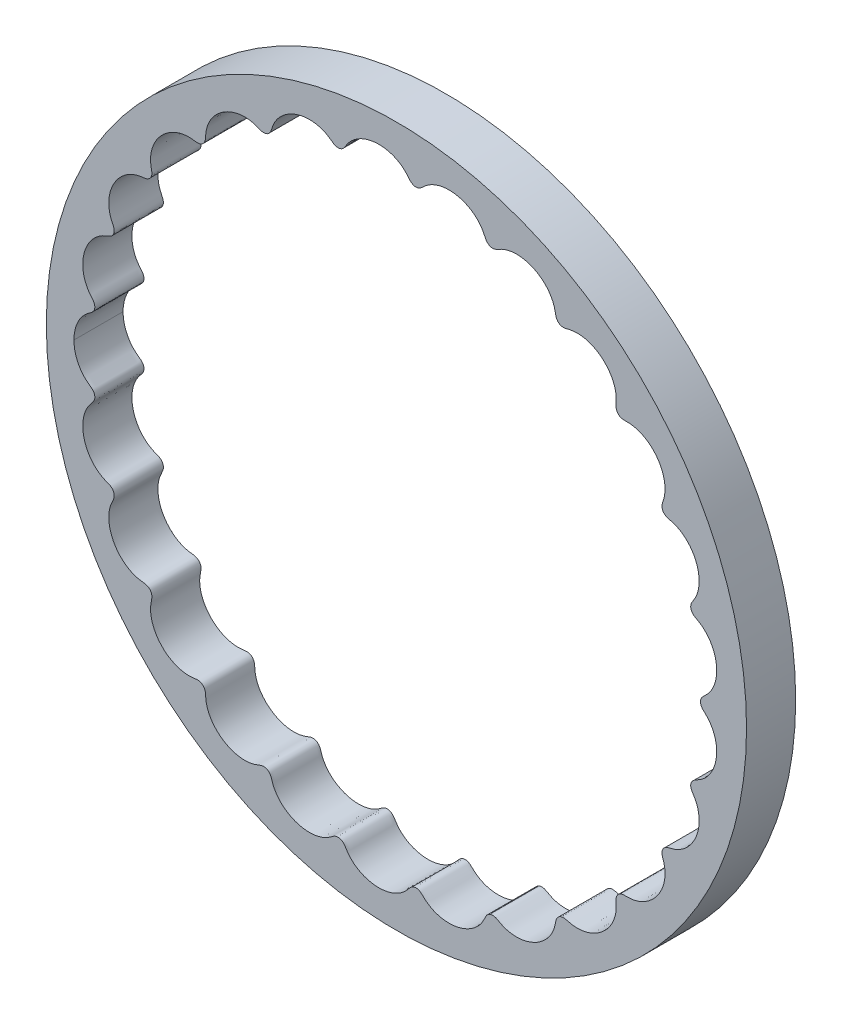
SolidWorks part; units mm, degrees
ref_plane "Plan de face" through (0, 0, 0) normal (0, 0, 1) x (1, 0, 0)
ref_plane "Plan de dessus" through (0, 0, 0) normal (0, 1, 0) x (1, 0, 0)
ref_plane "Plan de droite" through (0, 0, 0) normal (1, 0, 0) x (0, 0, -1)
sketch "Esquisse1" plane through (0, 0, 0) normal (0, 0, 1) x (1, 0, 0)
  line L0 (-1000, 0) -> (49000, 0) construction
  circle A1 centre (0, 0) radius 28.5
  spline S0 degree 4 poles (24.1426, 6.7991) (24.1177, 6.7609) (24.0692, 6.6836) (24.0004, 6.5645) (23.9483, 6.387) (23.9505, 6.1855) (24.0272, 5.9803) (24.1778, 5.8151) (24.3705, 5.7045) (24.5983, 5.5844) (24.8479, 5.4264) (25.1139, 5.2067) (25.3819, 4.9129) (25.6102, 4.583) (25.7961, 4.2235) (25.9371, 3.8403) (26.0305, 3.4429) (26.0756, 3.0373) (26.0716, 2.6291) (26.0179, 2.2244) (25.9151, 1.834) (25.7643, 1.4641) (25.5917, 1.1641) (25.4167, 0.9296) (25.2526, 0.7496) (25.1124, 0.6144) (24.9828, 0.4987) (24.8797, 0.3844) (24.8179, 0.2829) (24.7848, 0.2051) (24.7673, 0.1461) (24.7588, 0.1043) (24.7529, 0.0597) (24.7496, 0.0145) (24.7496, -0.0147) (24.7529, -0.06) (24.7589, -0.1048) (24.7675, -0.1468) (24.7852, -0.2061) (24.8185, -0.2842) (24.8808, -0.3859) (24.9847, -0.5005) (25.1148, -0.6166) (25.2554, -0.7525) (25.4198, -0.9333) (25.595, -1.1691) (25.7689, -1.4729) (25.9207, -1.8497) (26.0235, -2.2499) (26.0747, -2.6669) (26.0733, -3.0863) (26.0204, -3.5015) (25.917, -3.9063) (25.7644, -4.2943) (25.5662, -4.6548) (25.3259, -4.9815) (25.0816, -5.2331) (24.8519, -5.4186) (24.6671, -5.5402) (24.5395, -5.6139) (24.4102, -5.6846) (24.274, -5.758) (24.12, -5.8678) (23.9899, -6.0503) (23.9364, -6.2751) (23.9692, -6.4958) (24.0654, -6.6843) (24.1784, -6.8519) (24.2801, -7.019) (24.3936, -7.2353) (24.5034, -7.5077) (24.5951, -7.8454) (24.647, -8.2482) (24.6457, -8.6612) (24.576, -9.1855) (24.4176, -9.6961) (24.1747, -10.1766) (23.852, -10.6101) (23.5588, -10.9098) (23.241, -11.1578) (22.9466, -11.3291) (22.6921, -11.4408) (22.4727, -11.5135) (22.2939, -11.5615) (22.1013, -11.606) (21.9021, -11.6816) (21.7285, -11.8281) (21.6209, -12.0388) (21.6016, -12.2637) (21.6505, -12.4693) (21.7183, -12.6598) (21.7746, -12.8471) (21.8297, -13.085) (21.8672, -13.3762) (21.8707, -13.726) (21.8195, -14.1287) (21.7142, -14.528) (21.5148, -15.0178) (21.2331, -15.4721) (20.8771, -15.876) (20.4557, -16.2144) (20.0964, -16.4307) (19.7262, -16.5906) (19.3981, -16.6821) (19.1236, -16.7259) (18.8929, -16.7409) (18.7078, -16.7424) (18.5101, -16.7378) (18.2984, -16.7644) (18.0955, -16.8669) (17.9421, -17.0472) (17.8714, -17.2614) (17.8702, -17.4725) (17.8883, -17.6738) (17.8957, -17.8692) (17.8889, -18.1133) (17.8517, -18.4044) (17.7668, -18.7438) (17.6158, -19.1205) (17.4134, -19.4803) (17.1623, -19.8168) (16.8685, -20.1221) (16.5358, -20.3908) (16.1684, -20.6173) (15.771, -20.7957) (15.3688, -20.9145) (14.9702, -20.976) (14.6296, -20.9817) (14.3529, -20.9549) (14.1259, -20.9112) (13.9464, -20.866) (13.7558, -20.8128) (13.5435, -20.7889) (13.3222, -20.8417) (13.1314, -20.9817) (13.013, -21.1736) (12.9618, -21.3782) (12.9291, -21.5776) (12.887, -21.7685) (12.8188, -22.0029) (12.7093, -22.2752) (12.5416, -22.5821) (12.3006, -22.9086) (12.0142, -23.2057) (11.6866, -23.4682) (11.3255, -23.6897) (10.9359, -23.8661) (10.5233, -23.9928) (10.0937, -24.0655) (9.6744, -24.0792) (9.2731, -24.0382) (8.942, -23.9578) (8.6811, -23.862) (8.4724, -23.7624) (8.31, -23.6735) (8.1383, -23.575) (7.9372, -23.5018) (7.7049, -23.5021) (7.4781, -23.6007) (7.3169, -23.7729) (7.2208, -23.9706) (7.1156, -24.2034) (6.9743, -24.4604) (6.773, -24.7375) (6.4979, -25.0224) (6.1834, -25.2709) (5.8357, -25.4797) (5.4603, -25.6452) (5.0615, -25.7656) (4.6447, -25.8371) (4.2157, -25.8559) (3.7816, -25.8181) (3.3723, -25.7258) (2.9942, -25.5849) (2.6941, -25.4236) (2.4656, -25.2649) (2.2891, -25.1158) (2.1537, -24.9891) (2.0123, -24.8511) (1.8324, -24.7331) (1.553, -24.6659) (1.2621, -24.7546) (1.0754, -24.9576) (0.8891, -25.1941) (0.6967, -25.4018) (0.4476, -25.6153) (0.1257, -25.8218) (-0.2246, -25.9871) (-0.599, -26.1091) (-0.9909, -26.1853) (-1.3919, -26.2146) (-1.7962, -26.1958) (-2.1981, -26.1285) (-2.5915, -26.0119) (-2.9628, -25.849) (-3.3062, -25.6424) (-3.6154, -25.3948) (-3.8503, -25.1456) (-4.0231, -24.9087) (-4.157, -24.6911) (-4.2763, -24.5066) (-4.4563, -24.3545) (-4.6931, -24.2829) (-4.9238, -24.3097) (-5.115, -24.4061) (-5.2732, -24.5252) (-5.423, -24.6339) (-5.6174, -24.7592) (-5.864, -24.8876) (-6.1822, -25.0094) (-6.5751, -25.1011) (-6.9928, -25.1407) (-7.4281, -25.1231) (-7.8512, -25.0501) (-8.2556, -24.9263) (-8.636, -24.7563) (-8.9874, -24.5444) (-9.3058, -24.2932) (-9.5861, -24.0067) (-9.8229, -23.6892) (-9.9872, -23.3887) (-10.0948, -23.1158) (-10.1696, -22.8715) (-10.2411, -22.6635) (-10.3812, -22.4737) (-10.595, -22.3493) (-10.8256, -22.322) (-11.0338, -22.3709) (-11.2164, -22.4474) (-11.3887, -22.5149) (-11.6084, -22.5872) (-11.8793, -22.649) (-12.2179, -22.6866) (-12.6212, -22.6763) (-13.0353, -22.6095) (-13.4521, -22.4829) (-13.8453, -22.3049) (-14.2094, -22.0805) (-14.5395, -21.815) (-14.8313, -21.5131) (-15.0777, -21.1819) (-15.2753, -20.8275) (-15.4026, -20.5017) (-15.4765, -20.2177) (-15.5143, -19.9765) (-15.5318, -19.7817) (-15.5392, -19.5798) (-15.5656, -19.3704) (-15.6608, -19.166) (-15.8341, -19.0047) (-16.0476, -18.9266) (-16.2611, -18.9252) (-16.4568, -18.9543) (-16.6405, -18.9763) (-16.8713, -18.9908) (-17.1491, -18.9822) (-17.4862, -18.9332) (-17.8737, -18.8216) (-18.2576, -18.6527) (-18.6291, -18.4253) (-18.9648, -18.1541) (-19.2607, -17.8454) (-19.5135, -17.5053) (-19.7199, -17.1396) (-19.875, -16.7569) (-19.9769, -16.364) (-20.018, -16.0166) (-20.0178, -15.7231) (-19.9934, -15.4801) (-19.9613, -15.2872) (-19.9181, -15.0898) (-19.894, -14.8799) (-19.9394, -14.6589) (-20.0707, -14.462) (-20.2602, -14.3367) (-20.4672, -14.2852) (-20.6639, -14.2651) (-20.8473, -14.2402) (-21.0742, -14.196) (-21.3408, -14.1175) (-21.6546, -13.985) (-22.0015, -13.7794) (-22.3304, -13.5193) (-22.7055, -13.1302) (-23.0074, -12.6844) (-23.2291, -12.1981) (-23.3648, -11.6869) (-23.4186, -11.2774) (-23.4182, -10.8714) (-23.3703, -10.5248) (-23.296, -10.2407) (-23.211, -10.0117) (-23.1314, -9.8331) (-23.0402, -9.6526) (-22.9672, -9.4541) (-22.9601, -9.2287) (-23.0424, -9.0072) (-23.1982, -8.8407) (-23.3889, -8.7414) (-23.5777, -8.6723) (-23.7531, -8.5999) (-23.9662, -8.4963) (-24.2093, -8.3477) (-24.4803, -8.1356) (-24.7613, -7.8463) (-25.0085, -7.5133) (-25.2666, -7.049) (-25.4429, -6.5476) (-25.5339, -6.0256) (-25.5366, -5.4989) (-25.4855, -5.0889) (-25.3828, -4.696) (-25.2489, -4.3726) (-25.1052, -4.1164) (-24.9652, -3.9162) (-24.8431, -3.7634) (-24.7098, -3.6112) (-24.5919, -3.4354) (-24.5338, -3.2206) (-24.5604, -2.9926) (-24.6667, -2.797) (-24.8227, -2.6537) (-24.9897, -2.5393) (-25.1463, -2.4221) (-25.3325, -2.2638) (-25.5023, -2.0873) (-25.6545, -1.8958) (-25.7905, -1.6883) (-25.89, -1.512) (-25.979, -1.3255) (-26.0566, -1.1315) (-26.1214, -0.9307) (-26.1732, -0.7298) (-26.2073, -0.5457) (-26.2284, -0.3959) (-26.2405, -0.2557) (-26.247, -0.1691) (-26.2503, -0.0328) (-26.2503, 0.0323) (-26.2471, 0.1679) (-26.2407, 0.2542) (-26.2286, 0.3933) (-26.2078, 0.5423) (-26.1742, 0.7251) (-26.123, 0.925) (-26.0591, 1.1245) (-25.9824, 1.3176) (-25.8737, 1.547) (-25.7224, 1.8046) (-25.5451, 2.0414) (-25.3437, 2.2529) (-25.1596, 2.4115) (-25.0044, 2.5289) (-24.8386, 2.6423) (-24.6804, 2.7808) (-24.5546, 2.9935) (-24.5303, 3.2355) (-24.6, 3.4498) (-24.7118, 3.6094) (-24.804, 3.7191) (-24.9086, 3.8447) (-25.0204, 3.9911) (-25.1376, 4.1713) (-25.2521, 4.3886) (-25.3469, 4.6153) (-25.4409, 4.9075) (-25.515, 5.269) (-25.5464, 5.6988) (-25.509, 6.1899) (-25.401, 6.6704) (-25.2688, 7.0153) (-25.1588, 7.235) (-25.0985, 7.3418) knots 0 0 0 0 0 0.001685 0.003369 0.005054 0.006738 0.009006 0.011274 0.013086 0.014899 0.018524 0.022149 0.025774 0.029532 0.03329 0.037047 0.040805 0.044562 0.048319 0.052076 0.055834 0.059425 0.063017 0.064813 0.066609 0.068405 0.070201 0.071231 0.072261 0.072776 0.073291 0.073548 0.073806 0.074321 0.074838 0.075097 0.075356 0.075873 0.07639 0.077425 0.07846 0.080263 0.082066 0.083868 0.085671 0.089277 0.092883 0.09675 0.100617 0.104484 0.108351 0.112188 0.116026 0.119864 0.123701 0.127327 0.130952 0.132764 0.134577 0.135483 0.13639 0.138202 0.140296 0.142389 0.144459 0.146528 0.148331 0.150133 0.151935 0.153737 0.157342 0.160946 0.164812 0.168678 0.172544 0.180416 0.184421 0.188427 0.192432 0.195844 0.199256 0.200962 0.202668 0.204374 0.20608 0.208269 0.210458 0.212527 0.214596 0.216398 0.2182 0.220001 0.221803 0.225407 0.22901 0.232875 0.23674 0.240605 0.248477 0.252483 0.256489 0.260496 0.263908 0.26732 0.269026 0.270732 0.272438 0.274144 0.276335 0.278527 0.280595 0.282663 0.284464 0.286266 0.288067 0.289868 0.293471 0.297074 0.300938 0.304802 0.308666 0.31253 0.316537 0.320545 0.324552 0.328559 0.331971 0.335384 0.33709 0.338796 0.340502 0.342208 0.344401 0.346595 0.348662 0.350729 0.35253 0.354331 0.356132 0.357933 0.361536 0.365138 0.369001 0.372864 0.376727 0.38059 0.384598 0.388606 0.392614 0.396623 0.400035 0.403448 0.405154 0.40686 0.408567 0.410273 0.412468 0.414663 0.416905 0.419148 0.420948 0.422747 0.426346 0.429946 0.433545 0.437321 0.441097 0.444873 0.44865 0.452659 0.456668 0.460677 0.464686 0.468099 0.471512 0.473218 0.474925 0.476631 0.478338 0.480534 0.48273 0.48702 0.488749 0.490478 0.493937 0.497395 0.500854 0.50453 0.508207 0.511883 0.515559 0.519335 0.523111 0.526887 0.530662 0.534262 0.537861 0.54146 0.543259 0.545059 0.547301 0.549542 0.551738 0.553933 0.55564 0.557346 0.559053 0.560759 0.564172 0.567585 0.571593 0.575602 0.57961 0.583619 0.587396 0.591172 0.594949 0.598726 0.602325 0.605924 0.609523 0.611323 0.613123 0.615366 0.61761 0.619804 0.621998 0.623704 0.625411 0.627117 0.628823 0.632235 0.635648 0.639656 0.643663 0.647671 0.651679 0.655542 0.659406 0.663269 0.667133 0.670735 0.674338 0.676139 0.67794 0.679742 0.681543 0.68361 0.685678 0.68787 0.690063 0.691769 0.693475 0.695181 0.696887 0.700299 0.703711 0.707718 0.711725 0.715732 0.719739 0.723603 0.727468 0.731332 0.735197 0.7388 0.742403 0.744204 0.746006 0.747808 0.749609 0.751678 0.753746 0.755937 0.758127 0.759833 0.761539 0.763245 0.764951 0.768363 0.771775 0.775781 0.779787 0.783793 0.791664 0.795529 0.799395 0.80326 0.806864 0.810468 0.81227 0.814073 0.815875 0.817677 0.819746 0.821815 0.823999 0.826183 0.827931 0.82968 0.831429 0.833177 0.836675 0.840172 0.844094 0.848015 0.851937 0.859725 0.863591 0.867458 0.871324 0.874929 0.878534 0.880337 0.882139 0.883942 0.885745 0.887814 0.889884 0.891953 0.894023 0.895826 0.897629 0.899432 0.901235 0.904841 0.906644 0.908448 0.910381 0.912315 0.914249 0.916183 0.918117 0.92005 0.921017 0.921984 0.922951 0.923918 0.924879 0.925839 0.9268 0.927761 0.929682 0.931604 0.933525 0.935447 0.937368 0.93929 0.942875 0.94646 0.948253 0.950045 0.951838 0.95363 0.955683 0.957735 0.960756 0.962266 0.963777 0.964909 0.96604 0.968304 0.970568 0.972832 0.975095 0.977359 0.981887 0.986415 0.990943 0.995472 1 1 1 1 1 construction
  spline S1 degree 4 poles (24.75, 0) (24.75, -0.0119) (24.7507, -0.0298) (24.7529, -0.06) (24.7589, -0.1048) (24.7675, -0.1468) (24.7852, -0.2061) (24.8185, -0.2842) (24.8808, -0.3859) (24.9847, -0.5005) (25.1148, -0.6166) (25.2554, -0.7525) (25.4198, -0.9333) (25.595, -1.1691) (25.7689, -1.4729) (25.9207, -1.8497) (26.0235, -2.2499) (26.0747, -2.6669) (26.0733, -3.0863) (26.0204, -3.5015) (25.917, -3.9063) (25.7644, -4.2943) (25.5662, -4.6548) (25.3259, -4.9815) (25.0816, -5.2331) (24.8519, -5.4186) (24.6671, -5.5402) (24.5395, -5.6139) (24.4102, -5.6846) (24.274, -5.758) (24.12, -5.8678) (23.9899, -6.0503) (23.9364, -6.2751) (23.9692, -6.4958) (24.0654, -6.6843) (24.1784, -6.8519) (24.2801, -7.019) (24.3936, -7.2353) (24.5034, -7.5077) (24.5951, -7.8454) (24.647, -8.2482) (24.6457, -8.6612) (24.576, -9.1855) (24.4176, -9.6961) (24.1747, -10.1766) (23.852, -10.6101) (23.5588, -10.9098) (23.241, -11.1578) (22.9466, -11.3291) (22.6921, -11.4408) (22.4727, -11.5135) (22.2939, -11.5615) (22.1013, -11.606) (21.9021, -11.6816) (21.7285, -11.8281) (21.6209, -12.0388) (21.6016, -12.2637) (21.6505, -12.4693) (21.7183, -12.6598) (21.7746, -12.8471) (21.8297, -13.085) (21.8672, -13.3762) (21.8707, -13.726) (21.8195, -14.1287) (21.7142, -14.528) (21.5148, -15.0178) (21.2331, -15.4721) (20.8771, -15.876) (20.4557, -16.2144) (20.0964, -16.4307) (19.7262, -16.5906) (19.3981, -16.6821) (19.1236, -16.7259) (18.8929, -16.7409) (18.7078, -16.7424) (18.5101, -16.7378) (18.2984, -16.7644) (18.0955, -16.8669) (17.9421, -17.0472) (17.8714, -17.2614) (17.8702, -17.4725) (17.8883, -17.6738) (17.8957, -17.8692) (17.8889, -18.1133) (17.8517, -18.4044) (17.7668, -18.7438) (17.6158, -19.1205) (17.4134, -19.4803) (17.1623, -19.8168) (16.8685, -20.1221) (16.5358, -20.3908) (16.1684, -20.6173) (15.771, -20.7957) (15.3688, -20.9145) (14.9702, -20.976) (14.6296, -20.9817) (14.3529, -20.9549) (14.1259, -20.9112) (13.9464, -20.866) (13.7558, -20.8128) (13.5435, -20.7889) (13.3222, -20.8417) (13.1314, -20.9817) (13.013, -21.1736) (12.9618, -21.3782) (12.9291, -21.5776) (12.887, -21.7685) (12.8188, -22.0029) (12.7093, -22.2752) (12.5416, -22.5821) (12.3006, -22.9086) (12.0142, -23.2057) (11.6866, -23.4682) (11.3255, -23.6897) (10.9359, -23.8661) (10.5233, -23.9928) (10.0937, -24.0655) (9.6744, -24.0792) (9.2731, -24.0382) (8.942, -23.9578) (8.6811, -23.862) (8.4724, -23.7624) (8.31, -23.6735) (8.1383, -23.575) (7.9372, -23.5018) (7.7049, -23.5021) (7.4781, -23.6007) (7.3169, -23.7729) (7.2208, -23.9706) (7.1156, -24.2034) (6.9743, -24.4604) (6.773, -24.7375) (6.4979, -25.0224) (6.1834, -25.2709) (5.8357, -25.4797) (5.4603, -25.6452) (5.0615, -25.7656) (4.6447, -25.8371) (4.2157, -25.8559) (3.7816, -25.8181) (3.3723, -25.7258) (2.9942, -25.5849) (2.6941, -25.4236) (2.4656, -25.2649) (2.2891, -25.1158) (2.1537, -24.9891) (2.0123, -24.8511) (1.8324, -24.7331) (1.553, -24.6659) (1.2621, -24.7546) (1.0754, -24.9576) (0.8891, -25.1941) (0.6967, -25.4018) (0.4476, -25.6153) (0.1257, -25.8218) (-0.2246, -25.9871) (-0.599, -26.1091) (-0.9909, -26.1853) (-1.3919, -26.2146) (-1.7962, -26.1958) (-2.1981, -26.1285) (-2.5915, -26.0119) (-2.9628, -25.849) (-3.3062, -25.6424) (-3.6154, -25.3948) (-3.8503, -25.1456) (-4.0231, -24.9087) (-4.157, -24.6911) (-4.2763, -24.5066) (-4.4563, -24.3545) (-4.6931, -24.2829) (-4.9238, -24.3097) (-5.115, -24.4061) (-5.2732, -24.5252) (-5.423, -24.6339) (-5.6174, -24.7592) (-5.864, -24.8876) (-6.1822, -25.0094) (-6.5751, -25.1011) (-6.9928, -25.1407) (-7.4281, -25.1231) (-7.8512, -25.0501) (-8.2556, -24.9263) (-8.636, -24.7563) (-8.9874, -24.5444) (-9.3058, -24.2932) (-9.5861, -24.0067) (-9.8229, -23.6892) (-9.9872, -23.3887) (-10.0948, -23.1158) (-10.1696, -22.8715) (-10.2411, -22.6635) (-10.3812, -22.4737) (-10.595, -22.3493) (-10.8256, -22.322) (-11.0338, -22.3709) (-11.2164, -22.4474) (-11.3887, -22.5149) (-11.6084, -22.5872) (-11.8793, -22.649) (-12.2179, -22.6866) (-12.6212, -22.6763) (-13.0353, -22.6095) (-13.4521, -22.4829) (-13.8453, -22.3049) (-14.2094, -22.0805) (-14.5395, -21.815) (-14.8313, -21.5131) (-15.0777, -21.1819) (-15.2753, -20.8275) (-15.4026, -20.5017) (-15.4765, -20.2177) (-15.5143, -19.9765) (-15.5318, -19.7817) (-15.5392, -19.5798) (-15.5656, -19.3704) (-15.6608, -19.166) (-15.8341, -19.0047) (-16.0476, -18.9266) (-16.2611, -18.9252) (-16.4568, -18.9543) (-16.6405, -18.9763) (-16.8713, -18.9908) (-17.1491, -18.9822) (-17.4862, -18.9332) (-17.8737, -18.8216) (-18.2576, -18.6527) (-18.6291, -18.4253) (-18.9648, -18.1541) (-19.2607, -17.8454) (-19.5135, -17.5053) (-19.7199, -17.1396) (-19.875, -16.7569) (-19.9769, -16.364) (-20.018, -16.0166) (-20.0178, -15.7231) (-19.9934, -15.4801) (-19.9613, -15.2872) (-19.9181, -15.0898) (-19.894, -14.8799) (-19.9394, -14.6589) (-20.0707, -14.462) (-20.2602, -14.3367) (-20.4672, -14.2852) (-20.6639, -14.2651) (-20.8473, -14.2402) (-21.0742, -14.196) (-21.3408, -14.1175) (-21.6546, -13.985) (-22.0015, -13.7794) (-22.3304, -13.5193) (-22.7055, -13.1302) (-23.0074, -12.6844) (-23.2291, -12.1981) (-23.3648, -11.6869) (-23.4186, -11.2774) (-23.4182, -10.8714) (-23.3703, -10.5248) (-23.296, -10.2407) (-23.211, -10.0117) (-23.1314, -9.8331) (-23.0402, -9.6526) (-22.9672, -9.4541) (-22.9601, -9.2287) (-23.0424, -9.0072) (-23.1982, -8.8407) (-23.3889, -8.7414) (-23.5777, -8.6723) (-23.7531, -8.5999) (-23.9662, -8.4963) (-24.2093, -8.3477) (-24.4803, -8.1356) (-24.7613, -7.8463) (-25.0085, -7.5133) (-25.2666, -7.049) (-25.4429, -6.5476) (-25.5339, -6.0256) (-25.5366, -5.4989) (-25.4855, -5.0889) (-25.3828, -4.696) (-25.2489, -4.3726) (-25.1052, -4.1164) (-24.9652, -3.9162) (-24.8431, -3.7634) (-24.7098, -3.6112) (-24.5919, -3.4354) (-24.5338, -3.2206) (-24.5604, -2.9926) (-24.6667, -2.797) (-24.8227, -2.6537) (-24.9897, -2.5393) (-25.1463, -2.4221) (-25.3325, -2.2638) (-25.5023, -2.0873) (-25.6545, -1.8958) (-25.7905, -1.6883) (-25.89, -1.512) (-25.979, -1.3255) (-26.0566, -1.1315) (-26.1214, -0.9307) (-26.1732, -0.7298) (-26.2073, -0.5457) (-26.2284, -0.3959) (-26.2405, -0.2557) (-26.247, -0.1691) (-26.2495, -0.0667) (-26.25, -0.0223) (-26.25, 0) knots 0.074321 0.074321 0.074321 0.074321 0.074321 0.074838 0.075097 0.075356 0.075873 0.07639 0.077425 0.07846 0.080263 0.082066 0.083868 0.085671 0.089277 0.092883 0.09675 0.100617 0.104484 0.108351 0.112188 0.116026 0.119864 0.123701 0.127327 0.130952 0.132764 0.134577 0.135483 0.13639 0.138202 0.140296 0.142389 0.144459 0.146528 0.148331 0.150133 0.151935 0.153737 0.157342 0.160946 0.164812 0.168678 0.172544 0.180416 0.184421 0.188427 0.192432 0.195844 0.199256 0.200962 0.202668 0.204374 0.20608 0.208269 0.210458 0.212527 0.214596 0.216398 0.2182 0.220001 0.221803 0.225407 0.22901 0.232875 0.23674 0.240605 0.248477 0.252483 0.256489 0.260496 0.263908 0.26732 0.269026 0.270732 0.272438 0.274144 0.276335 0.278527 0.280595 0.282663 0.284464 0.286266 0.288067 0.289868 0.293471 0.297074 0.300938 0.304802 0.308666 0.31253 0.316537 0.320545 0.324552 0.328559 0.331971 0.335384 0.33709 0.338796 0.340502 0.342208 0.344401 0.346595 0.348662 0.350729 0.35253 0.354331 0.356132 0.357933 0.361536 0.365138 0.369001 0.372864 0.376727 0.38059 0.384598 0.388606 0.392614 0.396623 0.400035 0.403448 0.405154 0.40686 0.408567 0.410273 0.412468 0.414663 0.416905 0.419148 0.420948 0.422747 0.426346 0.429946 0.433545 0.437321 0.441097 0.444873 0.44865 0.452659 0.456668 0.460677 0.464686 0.468099 0.471512 0.473218 0.474925 0.476631 0.478338 0.480534 0.48273 0.48702 0.488749 0.490478 0.493937 0.497395 0.500854 0.50453 0.508207 0.511883 0.515559 0.519335 0.523111 0.526887 0.530662 0.534262 0.537861 0.54146 0.543259 0.545059 0.547301 0.549542 0.551738 0.553933 0.55564 0.557346 0.559053 0.560759 0.564172 0.567585 0.571593 0.575602 0.57961 0.583619 0.587396 0.591172 0.594949 0.598726 0.602325 0.605924 0.609523 0.611323 0.613123 0.615366 0.61761 0.619804 0.621998 0.623704 0.625411 0.627117 0.628823 0.632235 0.635648 0.639656 0.643663 0.647671 0.651679 0.655542 0.659406 0.663269 0.667133 0.670735 0.674338 0.676139 0.67794 0.679742 0.681543 0.68361 0.685678 0.68787 0.690063 0.691769 0.693475 0.695181 0.696887 0.700299 0.703711 0.707718 0.711725 0.715732 0.719739 0.723603 0.727468 0.731332 0.735197 0.7388 0.742403 0.744204 0.746006 0.747808 0.749609 0.751678 0.753746 0.755937 0.758127 0.759833 0.761539 0.763245 0.764951 0.768363 0.771775 0.775781 0.779787 0.783793 0.791664 0.795529 0.799395 0.80326 0.806864 0.810468 0.81227 0.814073 0.815875 0.817677 0.819746 0.821815 0.823999 0.826183 0.827931 0.82968 0.831429 0.833177 0.836675 0.840172 0.844094 0.848015 0.851937 0.859725 0.863591 0.867458 0.871324 0.874929 0.878534 0.880337 0.882139 0.883942 0.885745 0.887814 0.889884 0.891953 0.894023 0.895826 0.897629 0.899432 0.901235 0.904841 0.906644 0.908448 0.910381 0.912315 0.914249 0.916183 0.918117 0.92005 0.921017 0.921984 0.922951 0.923918 0.923918 0.923918 0.923918 0.923918
  spline S2 degree 4 poles (24.75, 0) (24.75, 0.0119) (24.7507, 0.0298) (24.7529, 0.06) (24.7589, 0.1048) (24.7675, 0.1468) (24.7852, 0.2061) (24.8185, 0.2842) (24.8808, 0.3859) (24.9847, 0.5005) (25.1148, 0.6166) (25.2554, 0.7525) (25.4198, 0.9333) (25.595, 1.1691) (25.7689, 1.4729) (25.9207, 1.8497) (26.0235, 2.2499) (26.0747, 2.6669) (26.0733, 3.0863) (26.0204, 3.5015) (25.917, 3.9063) (25.7644, 4.2943) (25.5662, 4.6548) (25.3259, 4.9815) (25.0816, 5.2331) (24.8519, 5.4186) (24.6671, 5.5402) (24.5395, 5.6139) (24.4102, 5.6846) (24.274, 5.758) (24.12, 5.8678) (23.9899, 6.0503) (23.9364, 6.2751) (23.9692, 6.4958) (24.0654, 6.6843) (24.1784, 6.8519) (24.2801, 7.019) (24.3936, 7.2353) (24.5034, 7.5077) (24.5951, 7.8454) (24.647, 8.2482) (24.6457, 8.6612) (24.576, 9.1855) (24.4176, 9.6961) (24.1747, 10.1766) (23.852, 10.6101) (23.5588, 10.9098) (23.241, 11.1578) (22.9466, 11.3291) (22.6921, 11.4408) (22.4727, 11.5135) (22.2939, 11.5615) (22.1013, 11.606) (21.9021, 11.6816) (21.7285, 11.8281) (21.6209, 12.0388) (21.6016, 12.2637) (21.6505, 12.4693) (21.7183, 12.6598) (21.7746, 12.8471) (21.8297, 13.085) (21.8672, 13.3762) (21.8707, 13.726) (21.8195, 14.1287) (21.7142, 14.528) (21.5148, 15.0178) (21.2331, 15.4721) (20.8771, 15.876) (20.4557, 16.2144) (20.0964, 16.4307) (19.7262, 16.5906) (19.3981, 16.6821) (19.1236, 16.7259) (18.8929, 16.7409) (18.7078, 16.7424) (18.5101, 16.7378) (18.2984, 16.7644) (18.0955, 16.8669) (17.9421, 17.0472) (17.8714, 17.2614) (17.8702, 17.4725) (17.8883, 17.6738) (17.8957, 17.8692) (17.8889, 18.1133) (17.8517, 18.4044) (17.7668, 18.7438) (17.6158, 19.1205) (17.4134, 19.4803) (17.1623, 19.8168) (16.8685, 20.1221) (16.5358, 20.3908) (16.1684, 20.6173) (15.771, 20.7957) (15.3688, 20.9145) (14.9702, 20.976) (14.6296, 20.9817) (14.3529, 20.9549) (14.1259, 20.9112) (13.9464, 20.866) (13.7558, 20.8128) (13.5435, 20.7889) (13.3222, 20.8417) (13.1314, 20.9817) (13.013, 21.1736) (12.9618, 21.3782) (12.9291, 21.5776) (12.887, 21.7685) (12.8188, 22.0029) (12.7093, 22.2752) (12.5416, 22.5821) (12.3006, 22.9086) (12.0142, 23.2057) (11.6866, 23.4682) (11.3255, 23.6897) (10.9359, 23.8661) (10.5233, 23.9928) (10.0937, 24.0655) (9.6744, 24.0792) (9.2731, 24.0382) (8.942, 23.9578) (8.6811, 23.862) (8.4724, 23.7624) (8.31, 23.6735) (8.1383, 23.575) (7.9372, 23.5018) (7.7049, 23.5021) (7.4781, 23.6007) (7.3169, 23.7729) (7.2208, 23.9706) (7.1156, 24.2034) (6.9743, 24.4604) (6.773, 24.7375) (6.4979, 25.0224) (6.1834, 25.2709) (5.8357, 25.4797) (5.4603, 25.6452) (5.0615, 25.7656) (4.6447, 25.8371) (4.2157, 25.8559) (3.7816, 25.8181) (3.3723, 25.7258) (2.9942, 25.5849) (2.6941, 25.4236) (2.4656, 25.2649) (2.2891, 25.1158) (2.1537, 24.9891) (2.0123, 24.8511) (1.8324, 24.7331) (1.553, 24.6659) (1.2621, 24.7546) (1.0754, 24.9576) (0.8891, 25.1941) (0.6967, 25.4018) (0.4476, 25.6153) (0.1257, 25.8218) (-0.2246, 25.9871) (-0.599, 26.1091) (-0.9909, 26.1853) (-1.3919, 26.2146) (-1.7962, 26.1958) (-2.1981, 26.1285) (-2.5915, 26.0119) (-2.9628, 25.849) (-3.3062, 25.6424) (-3.6154, 25.3948) (-3.8503, 25.1456) (-4.0231, 24.9087) (-4.157, 24.6911) (-4.2763, 24.5066) (-4.4563, 24.3545) (-4.6931, 24.2829) (-4.9238, 24.3097) (-5.115, 24.4061) (-5.2732, 24.5252) (-5.423, 24.6339) (-5.6174, 24.7592) (-5.864, 24.8876) (-6.1822, 25.0094) (-6.5751, 25.1011) (-6.9928, 25.1407) (-7.4281, 25.1231) (-7.8512, 25.0501) (-8.2556, 24.9263) (-8.636, 24.7563) (-8.9874, 24.5444) (-9.3058, 24.2932) (-9.5861, 24.0067) (-9.8229, 23.6892) (-9.9872, 23.3887) (-10.0948, 23.1158) (-10.1696, 22.8715) (-10.2411, 22.6635) (-10.3812, 22.4737) (-10.595, 22.3493) (-10.8256, 22.322) (-11.0338, 22.3709) (-11.2164, 22.4474) (-11.3887, 22.5149) (-11.6084, 22.5872) (-11.8793, 22.649) (-12.2179, 22.6866) (-12.6212, 22.6763) (-13.0353, 22.6095) (-13.4521, 22.4829) (-13.8453, 22.3049) (-14.2094, 22.0805) (-14.5395, 21.815) (-14.8313, 21.5131) (-15.0777, 21.1819) (-15.2753, 20.8275) (-15.4026, 20.5017) (-15.4765, 20.2177) (-15.5143, 19.9765) (-15.5318, 19.7817) (-15.5392, 19.5798) (-15.5656, 19.3704) (-15.6608, 19.166) (-15.8341, 19.0047) (-16.0476, 18.9266) (-16.2611, 18.9252) (-16.4568, 18.9543) (-16.6405, 18.9763) (-16.8713, 18.9908) (-17.1491, 18.9822) (-17.4862, 18.9332) (-17.8737, 18.8216) (-18.2576, 18.6527) (-18.6291, 18.4253) (-18.9648, 18.1541) (-19.2607, 17.8454) (-19.5135, 17.5053) (-19.7199, 17.1396) (-19.875, 16.7569) (-19.9769, 16.364) (-20.018, 16.0166) (-20.0178, 15.7231) (-19.9934, 15.4801) (-19.9613, 15.2872) (-19.9181, 15.0898) (-19.894, 14.8799) (-19.9394, 14.6589) (-20.0707, 14.462) (-20.2602, 14.3367) (-20.4672, 14.2852) (-20.6639, 14.2651) (-20.8473, 14.2402) (-21.0742, 14.196) (-21.3408, 14.1175) (-21.6546, 13.985) (-22.0015, 13.7794) (-22.3304, 13.5193) (-22.7055, 13.1302) (-23.0074, 12.6844) (-23.2291, 12.1981) (-23.3648, 11.6869) (-23.4186, 11.2774) (-23.4182, 10.8714) (-23.3703, 10.5248) (-23.296, 10.2407) (-23.211, 10.0117) (-23.1314, 9.8331) (-23.0402, 9.6526) (-22.9672, 9.4541) (-22.9601, 9.2287) (-23.0424, 9.0072) (-23.1982, 8.8407) (-23.3889, 8.7414) (-23.5777, 8.6723) (-23.7531, 8.5999) (-23.9662, 8.4963) (-24.2093, 8.3477) (-24.4803, 8.1356) (-24.7613, 7.8463) (-25.0085, 7.5133) (-25.2666, 7.049) (-25.4429, 6.5476) (-25.5339, 6.0256) (-25.5366, 5.4989) (-25.4855, 5.0889) (-25.3828, 4.696) (-25.2489, 4.3726) (-25.1052, 4.1164) (-24.9652, 3.9162) (-24.8431, 3.7634) (-24.7098, 3.6112) (-24.5919, 3.4354) (-24.5338, 3.2206) (-24.5604, 2.9926) (-24.6667, 2.797) (-24.8227, 2.6537) (-24.9897, 2.5393) (-25.1463, 2.4221) (-25.3325, 2.2638) (-25.5023, 2.0873) (-25.6545, 1.8958) (-25.7905, 1.6883) (-25.89, 1.512) (-25.979, 1.3255) (-26.0566, 1.1315) (-26.1214, 0.9307) (-26.1732, 0.7298) (-26.2073, 0.5457) (-26.2284, 0.3959) (-26.2405, 0.2557) (-26.247, 0.1691) (-26.2495, 0.0667) (-26.25, 0.0223) (-26.25, 0) knots 0.074321 0.074321 0.074321 0.074321 0.074321 0.074838 0.075097 0.075356 0.075873 0.07639 0.077425 0.07846 0.080263 0.082066 0.083868 0.085671 0.089277 0.092883 0.09675 0.100617 0.104484 0.108351 0.112188 0.116026 0.119864 0.123701 0.127327 0.130952 0.132764 0.134577 0.135483 0.13639 0.138202 0.140296 0.142389 0.144459 0.146528 0.148331 0.150133 0.151935 0.153737 0.157342 0.160946 0.164812 0.168678 0.172544 0.180416 0.184421 0.188427 0.192432 0.195844 0.199256 0.200962 0.202668 0.204374 0.20608 0.208269 0.210458 0.212527 0.214596 0.216398 0.2182 0.220001 0.221803 0.225407 0.22901 0.232875 0.23674 0.240605 0.248477 0.252483 0.256489 0.260496 0.263908 0.26732 0.269026 0.270732 0.272438 0.274144 0.276335 0.278527 0.280595 0.282663 0.284464 0.286266 0.288067 0.289868 0.293471 0.297074 0.300938 0.304802 0.308666 0.31253 0.316537 0.320545 0.324552 0.328559 0.331971 0.335384 0.33709 0.338796 0.340502 0.342208 0.344401 0.346595 0.348662 0.350729 0.35253 0.354331 0.356132 0.357933 0.361536 0.365138 0.369001 0.372864 0.376727 0.38059 0.384598 0.388606 0.392614 0.396623 0.400035 0.403448 0.405154 0.40686 0.408567 0.410273 0.412468 0.414663 0.416905 0.419148 0.420948 0.422747 0.426346 0.429946 0.433545 0.437321 0.441097 0.444873 0.44865 0.452659 0.456668 0.460677 0.464686 0.468099 0.471512 0.473218 0.474925 0.476631 0.478338 0.480534 0.48273 0.48702 0.488749 0.490478 0.493937 0.497395 0.500854 0.50453 0.508207 0.511883 0.515559 0.519335 0.523111 0.526887 0.530662 0.534262 0.537861 0.54146 0.543259 0.545059 0.547301 0.549542 0.551738 0.553933 0.55564 0.557346 0.559053 0.560759 0.564172 0.567585 0.571593 0.575602 0.57961 0.583619 0.587396 0.591172 0.594949 0.598726 0.602325 0.605924 0.609523 0.611323 0.613123 0.615366 0.61761 0.619804 0.621998 0.623704 0.625411 0.627117 0.628823 0.632235 0.635648 0.639656 0.643663 0.647671 0.651679 0.655542 0.659406 0.663269 0.667133 0.670735 0.674338 0.676139 0.67794 0.679742 0.681543 0.68361 0.685678 0.68787 0.690063 0.691769 0.693475 0.695181 0.696887 0.700299 0.703711 0.707718 0.711725 0.715732 0.719739 0.723603 0.727468 0.731332 0.735197 0.7388 0.742403 0.744204 0.746006 0.747808 0.749609 0.751678 0.753746 0.755937 0.758127 0.759833 0.761539 0.763245 0.764951 0.768363 0.771775 0.775781 0.779787 0.783793 0.791664 0.795529 0.799395 0.80326 0.806864 0.810468 0.81227 0.814073 0.815875 0.817677 0.819746 0.821815 0.823999 0.826183 0.827931 0.82968 0.831429 0.833177 0.836675 0.840172 0.844094 0.848015 0.851937 0.859725 0.863591 0.867458 0.871324 0.874929 0.878534 0.880337 0.882139 0.883942 0.885745 0.887814 0.889884 0.891953 0.894023 0.895826 0.897629 0.899432 0.901235 0.904841 0.906644 0.908448 0.910381 0.912315 0.914249 0.916183 0.918117 0.92005 0.921017 0.921984 0.922951 0.923918 0.923918 0.923918 0.923918 0.923918
  dimension "D1" = 57
extrude "Boss.-Extru.1" add sketch "Esquisse1" along normal blind 4
equation "\"R\" = 26'Radius of the rotor"
equation "\"E\"= 0.75'Eccentricity from input shaft to center of rotor"
equation "\"Rr\" = 0.5'Roller radius"
equation "\"N\" = 26'Amount of rollers"
equation "\"D1@Esquisse1\"=\"R\"*2+5"
